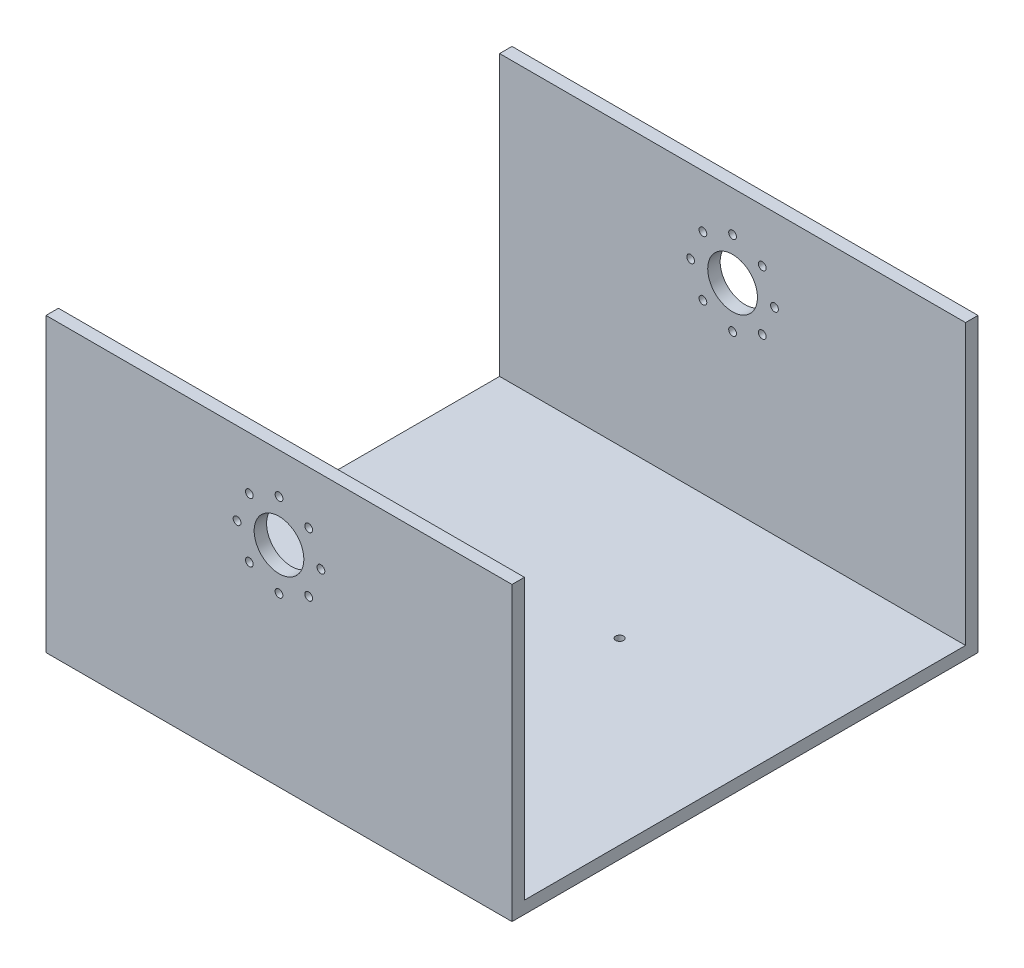
SolidWorks part; units mm, degrees
ref_plane "Front Plane" through (0, 0, 0) normal (0, 0, 1) x (1, 0, 0)
ref_plane "Top Plane" through (0, 0, 0) normal (0, 1, 0) x (1, 0, 0)
ref_plane "Right Plane" through (0, 0, 0) normal (1, 0, 0) x (0, 0, -1)
sketch "Sketch5" plane through (0, 0, 0) normal (0, 1, 0) x (1, 0, 0)
  line L1 (-150, 150) -> (150, 150)
  line L2 (-150, 150) -> (-150, -150)
  line L3 (-150, -150) -> (150, -150)
  line L4 (150, 150) -> (150, -150)
  line L5 (-150, 150) -> (150, -150) construction
  line L6 (-150, -150) -> (150, 150) construction
  point P0 (0, 0)
  dimension "D1" = 300
  dimension "D2" = 300
extrude "Boss-Extrude4" add sketch "Sketch5" along normal blind 8
sketch "Sketch6" plane through (0, 8, 0) normal (0, 1, 0) x (1, 0, 0)
  line L0 (0, 0) -> (-44.8869, 44.8869) construction
  circle A0 centre (0, 0) radius 5
  circle A1 centre (-34.6267, 34.6267) radius 2.5
  circle A2 centre (34.6267, 34.6267) radius 2.5
  circle A3 centre (34.6267, -34.6267) radius 2.5
  circle A4 centre (-34.6267, -34.6267) radius 2.5
  point P15 (0, 0)
  dimension "D2" = 5
  dimension "D3" = 10
  dimension "D1" = 48.9695
  dimension "D4" = 4
extrude "Cut-Extrude2" cut sketch "Sketch6" against normal blind 16
sketch "Sketch7" plane through (0, 8, 0) normal (0, 1, 0) x (1, 0, 0)
  line L0 (150, -150) -> (150, 150) construction
  line L1 (-150, 150) -> (150, 150)
  line L2 (-150, 150) -> (-150, 142)
  line L3 (-150, 142) -> (150, 142)
  line L4 (150, 150) -> (150, 142)
  line L6 (-150, -150) -> (150, -150)
  line L7 (-150, -150) -> (-150, -142)
  line L8 (-150, -142) -> (150, -142)
  line L9 (150, -150) -> (150, -142)
  dimension "D1" = 8
  dimension "D2" = 8
extrude "Boss-Extrude5" add sketch "Sketch7" along normal blind 180
sketch "Sketch9" plane through (0, 0, 150) normal (0, 0, 1) x (1, 0, 0)
  circle A0 centre (0, 135) radius 16
  dimension "D2" = 32
  dimension "D1" = 135
extrude "Cut-Extrude3" cut sketch "Sketch9" against normal blind 350
sketch "Sketch11" plane through (0, 0, 150) normal (0, 0, 1) x (1, 0, 0)
  circle A0 centre (0, 162) radius 2.5
  circle A1 centre (0, 135) radius 16 construction
  circle A2 centre (19.0919, 154.0919) radius 2.5
  circle A3 centre (27, 135) radius 2.5
  circle A4 centre (19.0919, 115.9081) radius 2.5
  circle A5 centre (0, 108) radius 2.5
  circle A6 centre (-19.0919, 115.9081) radius 2.5
  circle A7 centre (-27, 135) radius 2.5
  circle A8 centre (-19.0919, 154.0919) radius 2.5
  point P20 (0, 135)
  dimension "D2" = 5
  dimension "D1" = 27
  dimension "D3" = 8
extrude "Cut-Extrude4" cut sketch "Sketch11" against normal blind 310
